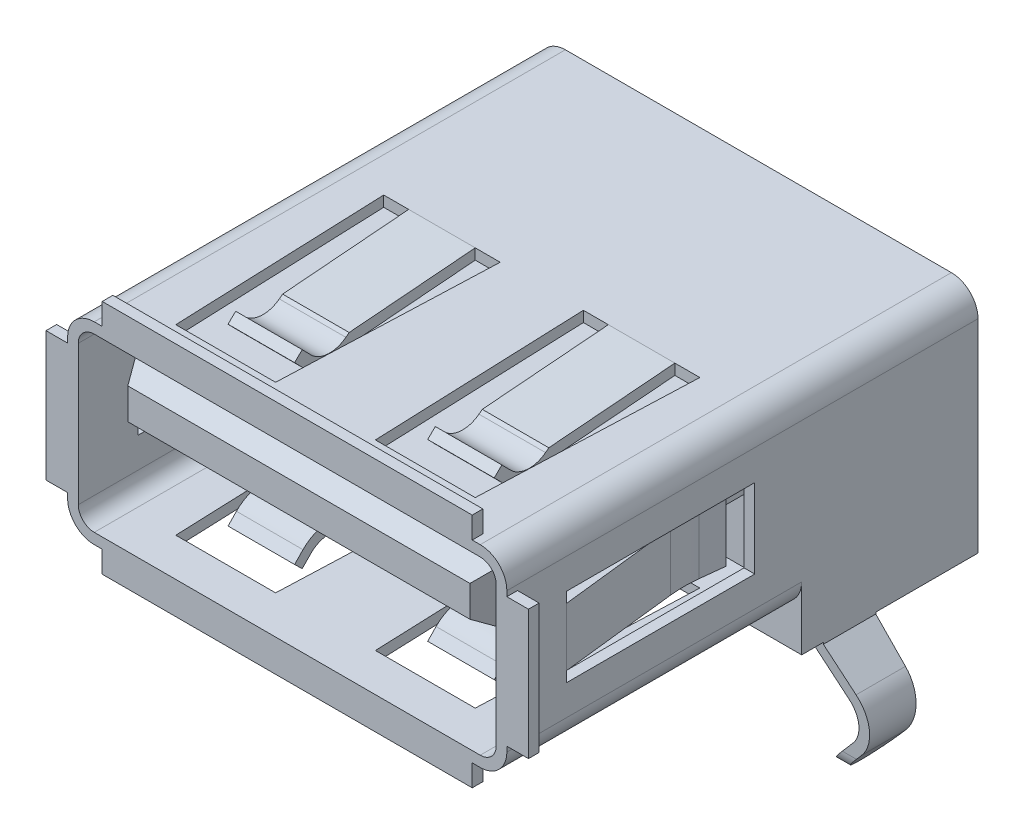
SolidWorks part; units mm, degrees
ref_plane "Front" through (0, 0, 0) normal (0, 0, 1) x (1, 0, 0)
ref_plane "Top" through (0, 0, 0) normal (0, 1, 0) x (1, 0, 0)
ref_plane "Side" through (0, 0, 0) normal (1, 0, 0) x (0, 0, -1)
sketch "Sketch1" plane through (0, 0, 0) normal (0, 1, 0) x (1, 0, 0)
  line L0 (6.6, -7.08) -> (-6.6, 7.08) construction
  line L1 (-6.6, 7.08) -> (6.6, 7.08)
  line L2 (-6.6, 7.08) -> (-6.6, -7.08)
  line L3 (-6.6, -7.08) -> (6.6, -7.08)
  line L4 (6.6, 7.08) -> (6.6, -7.08)
  dimension "D1" = 13.2
  dimension "D2" = 14.16
extrude "Base" add sketch "Sketch1" along normal blind 5.8
sketch "Sketch3" plane through (0, 0, 7.08) normal (0, 0, 1) x (1, 0, 0)
  line L0 (-6.6, 5.8) -> (6.6, 5.8) construction
  line L1 (-5.56, 5.8) -> (5.56, 5.8)
  line L2 (-5.56, 5.8) -> (-5.56, 6.45)
  line L3 (-5.56, 6.45) -> (5.56, 6.45)
  line L4 (5.56, 5.8) -> (5.56, 6.45)
  line L5 (6.6, 5.8) -> (6.6, 0) construction
  line L6 (6.6, 4.845) -> (7.25, 4.845)
  line L7 (6.6, 4.845) -> (6.6, 0.955)
  line L8 (6.6, 0.955) -> (7.25, 0.955)
  line L9 (7.25, 4.845) -> (7.25, 0.955)
  line L10 (0, 6.45) -> (0, 5.8) construction
  line L11 (6.6, 2.9) -> (7.25, 2.9) construction
  line L12 (-6.6, 5.8) -> (6.6, 0) construction
  line L13 (0, 2.9) -> (3.5942, 2.9) construction
  line L14 (5.56, 0) -> (5.56, -0.65)
  line L15 (-5.56, -0.65) -> (5.56, -0.65)
  line L16 (-5.56, 0) -> (-5.56, -0.65)
  line L17 (-5.56, 0) -> (5.56, 0)
  line L18 (0, 2.9) -> (0, 5.1458) construction
  line L19 (-7.25, 4.845) -> (-7.25, 0.955)
  line L20 (-6.6, 0.955) -> (-7.25, 0.955)
  line L21 (-6.6, 4.845) -> (-6.6, 0.955)
  line L22 (-6.6, 4.845) -> (-7.25, 4.845)
  dimension "D1" = 3.89
  dimension "D2" = 11.12
  dimension "D3" = 0.65
extrude "Front Tabs" add sketch "Sketch3" against normal blind 0.32
fillet "Corner Fillets" radius 0.8 4 edges at (-6.6, 5.8, 0) (-6.6, 0, 0) (6.6, 0, 0) (6.6, 5.8, 0)
ref_plane "Position 1 Plane" through (-3.5, 0, 0) normal (1, 0, 0) x (0, 0, -1)
sketch "Sketch8" plane through (0, 0, 7.08) normal (0, 0, 1) x (1, 0, 0)
  line L0 (-6.28, 5) -> (-6.28, 0.8)
  line L1 (-5.8, 0.32) -> (5.8, 0.32)
  line L2 (-5.8, 5.48) -> (5.8, 5.48)
  line L3 (6.28, 0.8) -> (6.28, 5)
  arc A16 (6.28, 5) -> (5.8, 5.48) centre (5.8, 5) ccw
  arc A17 (5.8, 0.32) -> (6.28, 0.8) centre (5.8, 0.8) ccw
  arc A18 (-6.28, 0.8) -> (-5.8, 0.32) centre (-5.8, 0.8) ccw
  arc A19 (-5.8, 5.48) -> (-6.28, 5) centre (-5.8, 5) ccw
extrude "Contact Area Cutout" cut sketch "Sketch8" against normal blind 8.85
sketch "Sketch18" plane through (0, 0, -7.08) normal (0, 0, -1) x (-1, 0, 0)
  line L0 (-6.6, 0.8) -> (-6.6, -1.1)
  line L1 (-6.6, -1.1) -> (6.6, -1.1)
  line L2 (6.6, -1.1) -> (6.6, 0.8)
  line L3 (-5.8, 0) -> (5.8, 0) construction
  line L4 (-5.8, 0) -> (5.8, 0)
  line L5 (-5.8, 5.8) -> (5.8, 5.8) construction
  arc A0 (-6.6, 0.8) -> (-5.8, 0) centre (-5.8, 0.8) ccw construction
  arc A1 (5.8, 0) -> (6.6, 0.8) centre (5.8, 0.8) ccw construction
  arc A2 (-6.6, 0.8) -> (-5.8, 0) centre (-5.8, 0.8) ccw
  arc A3 (5.8, 0) -> (6.6, 0.8) centre (5.8, 0.8) ccw
  dimension "D1" = 6.9
extrude "Back Step" add sketch "Sketch18" against normal blind 5.3
sketch "Sketch19" plane through (0, 0, 0) normal (0, -1, 0) x (1, 0, 0)
  line L0 (6.6, -1.78) -> (-6.6, -1.78) construction
  line L1 (1.2, -1.78) -> (-1.2, -1.78)
  line L2 (1.2, -1.78) -> (1.2, 1.32)
  line L3 (1.2, 1.32) -> (-1.2, 1.32)
  line L4 (-1.2, -1.78) -> (-1.2, 1.32)
  line L5 (0, 1.32) -> (0, -1.78) construction
  dimension "D1" = 3.1
  dimension "D2" = 2.4
extrude "Bottom Step" add sketch "Sketch19" along normal up to surface (1.1 mm away) up to face at (0, -1.1, -4.43)
ref_plane "Ground Tail Plane" through (0, 0, -3.22) normal (0, 0, 1) x (1, 0, 0)
sketch "Sketch10" plane through (0, 0, -3.22) normal (0, 0, 1) x (1, 0, 0)
  line L0 (6.6, -1.15) -> (6.6, -1.1)
  line L1 (-6.7465, -4.6) -> (-6.505, -4.39)
  line L2 (-6.6, -1.1) -> (-6.28, -1.1)
  line L3 (-6.28, -1.1) -> (-6.28, -1.2897)
  line L4 (6.6, -1.15) -> (7.5376, -2.0196)
  line L5 (7.622, -3.5932) -> (6.7465, -4.6)
  line L6 (7.3806, -3.3833) -> (6.505, -4.39)
  line L7 (6.28, -1.2897) -> (7.32, -2.2542)
  line L8 (6.28, -1.1) -> (6.28, -1.2897)
  line L9 (-6.28, -1.2897) -> (-7.32, -2.2542)
  line L10 (-7.3806, -3.3833) -> (-6.505, -4.39)
  line L11 (-7.622, -3.5932) -> (-6.7465, -4.6)
  line L12 (6.6, -1.1) -> (6.28, -1.1)
  line L13 (0, 0) -> (0, -2.9377) construction
  line L14 (-6.6, -1.15) -> (-7.5376, -2.0196)
  line L15 (-6.6, -1.1) -> (-6.6, -1.15)
  line L16 (6.6, 0.8) -> (6.6, -1.1) construction
  line L25 (6.6, -1.1) -> (1.2, -1.1) construction
  line L27 (6.7465, -4.6) -> (6.505, -4.39)
  arc A0 (7.5376, -2.0196) -> (7.622, -3.5932) centre (6.7674, -2.85) cw
  arc A1 (7.32, -2.2542) -> (7.3806, -3.3833) centre (6.7674, -2.85) cw
  arc A2 (-7.32, -2.2542) -> (-7.3806, -3.3833) centre (-6.7674, -2.85) ccw
  arc A3 (-7.5376, -2.0196) -> (-7.622, -3.5932) centre (-6.7674, -2.85) ccw
  dimension "D2" = 13.01
  dimension "D5" = 15.8
  dimension "D7" = 1.1326
  dimension "D1" = 3.5
  dimension "D3" = 0.32
  dimension "D6" = 1.75
  dimension "D4" = 0.05
  dimension "D8" = 0.32
extrude "Ground Tail" add sketch "Sketch10" along normal mid plane 1.58
sketch "Sketch11" plane through (0, 0, 0) normal (1, 0, 0) x (0, 0, -1)
  line L0 (2.43, -1.1) -> (2.5709, -3.7841)
  line L1 (2.43, -1.15) -> (2.43, -1.1) construction
  line L2 (3.22, -4.4) -> (3.22, -1.7369) construction
  line L4 (4.01, -1.1) -> (3.8691, -3.7841)
  line L6 (2.43, -1.1) -> (2.43, -4.7)
  line L7 (4.01, -1.1) -> (4.01, -4.7)
  line L10 (4.01, -4.7) -> (2.43, -4.7)
  arc A0 (2.5709, -3.7841) -> (3.22, -4.4) centre (3.22, -3.75) ccw
  arc A1 (3.8691, -3.7841) -> (3.22, -4.4) centre (3.22, -3.75) cw
  dimension "D2" = 0.65
  dimension "D1" = 3.6
extrude "Ground Tail Shape" cut sketch "Sketch11" against normal mid plane 16
sketch "Sketch12" plane through (0, 5.8, 0) normal (0, 1, 0) x (-1, 0, 0)
  line L0 (0, 0) -> (0, 5.7946) construction
  line L1 (4.5, 5.93) -> (4.75, -0.57)
  line L2 (3, 4.5748) -> (3, 0.3752) construction
  line L3 (1.5, 5.93) -> (1.25, -0.57)
  line L4 (4.5, 5.93) -> (1.5, 5.93)
  line L5 (4.75, -0.57) -> (1.25, -0.57)
  line L6 (6.6, 7.08) -> (7.25, 7.08) construction
  line L7 (-4.75, -0.57) -> (-1.25, -0.57)
  line L8 (-4.5, 5.93) -> (-1.5, 5.93)
  line L9 (-1.5, 5.93) -> (-1.25, -0.57)
  line L10 (-4.5, 5.93) -> (-4.75, -0.57)
  dimension "D1" = 3.5
  dimension "D2" = 3
  dimension "D3" = 6.5
  dimension "D4" = 7.65
  dimension "D5" = 3
extrude "Top/Bottom Flange Cutout" cut sketch "Sketch12" against normal through all
ref_plane "Top/Bottom Flange Plane" through (-3, 0, 0) normal (1, 0, 0) x (0, 0, -1)
sketch "Sketch13" plane through (-3, 0, 0) normal (1, 0, 0) x (0, 0, -1)
  line L0 (0.57, 5.8) -> (-3.2191, 5.4912)
  line L1 (-7.08, 5.8) -> (7.08, 5.8) construction
  line L2 (-3.2191, 5.4912) -> (-3.3183, 5.4151)
  line L3 (-4.3776, 5.4913) -> (-4.63, 5.75)
  line L4 (-4.6066, 5.2678) -> (-4.859, 5.5265)
  line L5 (-3.0992, 5.1799) -> (-3.1236, 5.1612)
  line L6 (0.57, 5.4789) -> (-3.0992, 5.1799)
  line L7 (-4.859, 5.5265) -> (-4.63, 5.75)
  line L8 (0.57, 5.8) -> (0.57, 5.4789)
  line L9 (1.1162, 5.8) -> (1.1162, 0) construction
  line L10 (1.78, 0) -> (-7.08, 0) construction
  line L11 (1.1162, 2.9) -> (-5.283, 2.9) construction
  line L12 (0.57, 0) -> (0.57, 0.3211)
  line L13 (-4.859, 0.2735) -> (-4.63, 0.05)
  line L14 (0.57, 0.3211) -> (-3.0992, 0.6201)
  line L15 (-3.0992, 0.6201) -> (-3.1236, 0.6388)
  line L16 (-4.6066, 0.5322) -> (-4.859, 0.2735)
  line L17 (-4.3776, 0.3087) -> (-4.63, 0.05)
  line L18 (-3.2191, 0.3088) -> (-3.3183, 0.3849)
  line L19 (0.57, 0) -> (-3.2191, 0.3088)
  arc A0 (-3.3183, 5.4151) -> (-4.3776, 5.4913) centre (-3.805, 6.05) cw
  arc A1 (-3.1236, 5.1612) -> (-4.6066, 5.2678) centre (-3.805, 6.05) cw
  arc A2 (-3.1236, 0.6388) -> (-4.6066, 0.5322) centre (-3.805, -0.25) ccw
  arc A3 (-3.3183, 0.3849) -> (-4.3776, 0.3087) centre (-3.805, -0.25) ccw
  dimension "D3" = 0.8
  dimension "D6" = 0.25
  dimension "D2" = 4.375
  dimension "D4" = 5.2
  dimension "D5" = 0.05
  dimension "D1" = 0.32
extrude "Top/Bottom Flange" add sketch "Sketch13" along normal mid plane 2
pattern_linear "Top/Bottom Flange Pattern" count 2 spacing 6 along (1, 0, 0) of "Top/Bottom Flange"
sketch "Sketch14" plane through (6.6, 0, 0) normal (1, 0, 0) x (0, 0, -1)
  line L0 (0.37, 2.9) -> (-5.28, 2.9) construction
  line L1 (-5.28, 4.09) -> (0.37, 4.09)
  line L2 (-5.28, 4.09) -> (-5.28, 1.71)
  line L3 (-5.28, 1.71) -> (0.37, 1.71)
  line L4 (0.37, 4.09) -> (0.37, 1.71)
  line L5 (-7.08, 5.8) -> (-7.08, 6.45) construction
  line L6 (1.1162, 2.9) -> (-5.283, 2.9) construction
  dimension "D1" = 2.38
  dimension "D2" = 5.65
  dimension "D3" = 1.8
extrude "Side Flange Cutout" cut sketch "Sketch14" against normal through all
ref_plane "Mid Plane" through (0, 2.9, 0) normal (0, 1, 0) x (-1, 0, 0)
sketch "Sketch15" plane through (0, 2.9, 0) normal (0, 1, 0) x (-1, 0, 0)
  line L0 (6.6, 5.28) -> (6.199, 1.7537)
  line L1 (6.1988, 0.9078) -> (6.2813, 0.18)
  line L2 (6.6, 5.28) -> (6.28, 5.28) construction
  line L3 (6.6, 7.08) -> (6.6, -7.08) construction
  line L4 (5.8809, 0.8718) -> (5.9633, 0.144)
  line L5 (6.282, 5.3162) -> (5.8811, 1.7898)
  line L6 (6.282, 5.3162) -> (6.6, 5.28)
  line L7 (5.9633, 0.144) -> (6.2813, 0.18)
  line L8 (0, 0) -> (0, 6.0458) construction
  line L9 (-5.9633, 0.144) -> (-6.2813, 0.18)
  line L10 (-6.282, 5.3162) -> (-6.6, 5.28)
  line L11 (-6.282, 5.3162) -> (-5.8811, 1.7898)
  line L12 (-5.8809, 0.8718) -> (-5.9633, 0.144)
  line L13 (-6.1988, 0.9078) -> (-6.2813, 0.18)
  line L14 (-6.6, 5.28) -> (-6.199, 1.7537)
  arc A0 (6.199, 1.7537) -> (6.1988, 0.9078) centre (9.925, 1.33) ccw
  arc A1 (5.8811, 1.7898) -> (5.8809, 0.8718) centre (9.925, 1.33) ccw
  arc A2 (-5.8811, 1.7898) -> (-5.8809, 0.8718) centre (-9.925, 1.33) cw
  arc A3 (-6.199, 1.7537) -> (-6.1988, 0.9078) centre (-9.925, 1.33) cw
  dimension "D2" = 3.75
  dimension "D3" = 3.95
  dimension "D4" = 3.325
  dimension "D1" = 5.1
  dimension "D5" = 0.32
extrude "Side Flange" add sketch "Sketch15" along normal mid plane 1.75
sketch "Sketch16" plane through (0, 0, -1.77) normal (0, 0, 1) x (1, 0, 0)
  line L0 (0, 4.72) -> (0, 2.92) construction
  line L1 (-5.575, 4.72) -> (5.575, 4.72)
  line L2 (-5.575, 4.72) -> (-5.575, 2.92)
  line L3 (-5.575, 2.92) -> (5.575, 2.92)
  line L4 (5.575, 4.72) -> (5.575, 2.92)
  line L5 (5.56, 5.8) -> (5.8, 5.8) construction
  dimension "D2" = 2.88
  dimension "D3" = 1.8
  dimension "D4" = 11.15
extrude "Contact Guide" add sketch "Sketch16" along normal blind 8.5
chamfer "Contact Guide Lead-in" distance 0.75 angle 30 4 edges at (0, 2.92, 6.73) (-5.575, 3.82, 6.73) (0, 4.72, 6.73) (5.575, 3.82, 6.73)
sketch "Sketch17" plane through (-3.5, 0, 0) normal (1, 0, 0) x (0, 0, -1)
  line L0 (1.77, 3.91) -> (1.77, 3.65)
  line L1 (1.77, 4.72) -> (1.77, 2.92) construction
  line L2 (1.77, 3.65) -> (0.52, 3.65)
  line L3 (0.52, 3.65) -> (-3.0429, 2.5075)
  line L4 (-4.9462, 2.7571) -> (-5.48, 3.1)
  line L9 (1.77, 0.8) -> (1.77, 5) construction
  line L10 (-4.8057, 2.9758) -> (-5.3395, 3.3187)
  line L11 (0.4793, 3.91) -> (-3.1223, 2.755)
  line L12 (1.77, 3.91) -> (0.4793, 3.91)
  line L13 (-5.98, 2.92) -> (1.77, 2.92) construction
  line L15 (-5.48, 3.1) -> (-5.3395, 3.3187)
  arc A0 (-3.0429, 2.5075) -> (-4.9462, 2.7571) centre (-3.73, 4.65) cw
  arc A1 (-3.1223, 2.755) -> (-4.8057, 2.9758) centre (-3.73, 4.65) cw
  dimension "D5" = 2.25
  dimension "D6" = 1
  dimension "D7" = 4.25
  dimension "D2" = 0.73
  dimension "D4" = 1.25
  dimension "D8" = 0.55
  dimension "D9" = 6
  dimension "D10" = 0.26
extrude "Contact 1" add sketch "Sketch17" along normal mid plane 0.66
pattern_linear "Contact Pattern2" count 2 spacing 2.5 along (1, 0, 0) of "Contact 1"
pattern_linear "Contact Pattern3" count 2 spacing 4.5 along (1, 0, 0) of "Contact 1"
pattern_linear "Contact Pattern4" count 2 spacing 7 along (1, 0, 0) of "Contact 1"
sketch "Sketch20" plane through (0, -1.1, 0) normal (0, -1, 0) x (1, 0, 0)
  line L0 (-3.5, -5.815) -> (-3.5, -6.125) construction
  line L1 (-3.16, -5.815) -> (-3.84, -5.815)
  line L2 (-3.16, -5.815) -> (-3.16, -6.125)
  line L3 (-3.16, -6.125) -> (-3.84, -6.125)
  line L4 (-3.84, -5.815) -> (-3.84, -6.125)
  line L5 (-3.16, -5.97) -> (-3.84, -5.97) construction
  line L6 (-3.5, -0.8817) -> (-3.5, 0.8817) construction
  line L7 (3.905, -3.22) -> (-3.905, -3.22) construction
  line L9 (3.16, -5.815) -> (3.16, -6.125)
  line L10 (3.84, -5.815) -> (3.16, -5.815)
  line L11 (3.84, -5.815) -> (3.84, -6.125)
  line L12 (3.84, -6.125) -> (3.16, -6.125)
  line L13 (-1.34, -5.815) -> (-1.34, -6.125)
  line L14 (-0.66, -5.815) -> (-1.34, -5.815)
  line L15 (-0.66, -5.815) -> (-0.66, -6.125)
  line L16 (-0.66, -6.125) -> (-1.34, -6.125)
  line L17 (0.66, -5.815) -> (0.66, -6.125)
  line L18 (1.34, -5.815) -> (0.66, -5.815)
  line L19 (1.34, -5.815) -> (1.34, -6.125)
  line L20 (1.34, -6.125) -> (0.66, -6.125)
  dimension "D1" = 0.68
  dimension "D2" = 0.31
  dimension "D3" = 2.75
extrude "Tails" add sketch "Sketch20" along normal blind 3.3
